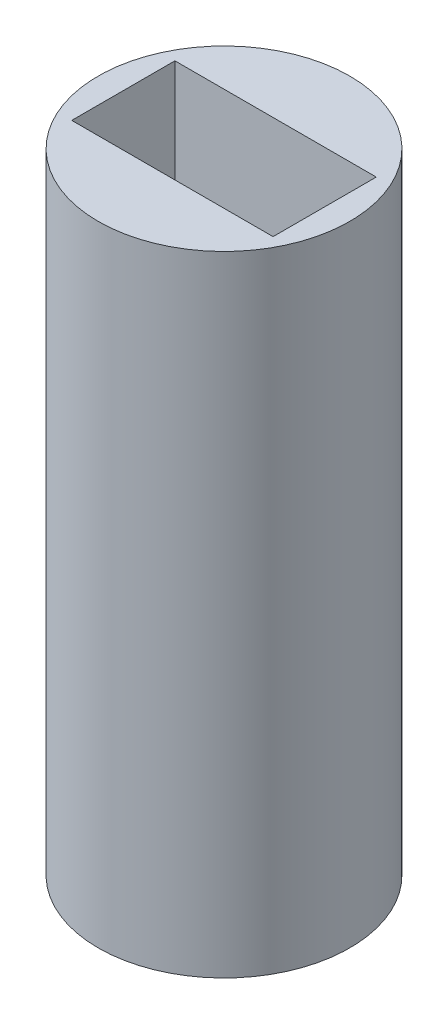
SolidWorks part; units mm, degrees
ref_plane "Front Plane" through (0, 0, 0) normal (0, 0, 1) x (1, 0, 0)
ref_plane "Top Plane" through (0, 0, 0) normal (0, 1, 0) x (1, 0, 0)
ref_plane "Right Plane" through (0, 0, 0) normal (1, 0, 0) x (0, 0, -1)
sketch "Sketch1" plane through (0, 0, 0) normal (0, 1, 0) x (1, 0, 0)
  circle A0 centre (0, 0) radius 5
  dimension "D1" = 10
extrude "Boss-Extrude1" add sketch "Sketch1" along normal blind 25
sketch "Sketch2" plane through (0, 0, 0) normal (0, 0, 1) x (1, 0, 0)
  line L0 (-4, 11.5) -> (-4, 25)
  line L1 (5, 25) -> (-5, 25) construction
  line L2 (4, 11.5) -> (4, 25)
  line L3 (-4, 25) -> (4, 25)
  arc A0 (-4, 11.5) -> (4, 11.5) centre (0, 11.5) ccw
  dimension "D1" = 8
  dimension "D2" = 13.5
extrude "Cut-Extrude1" cut sketch "Sketch2" against normal mid plane 4.1
